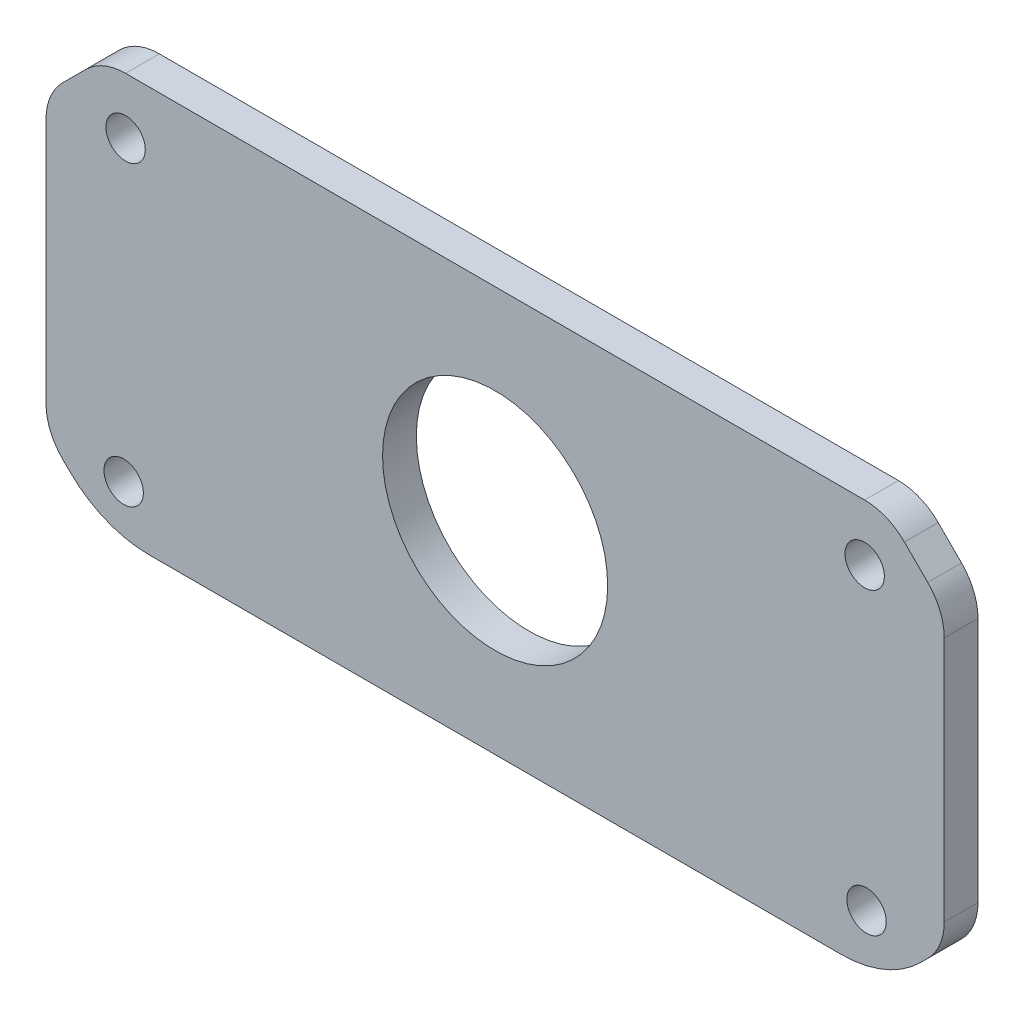
SolidWorks part; units mm, degrees
ref_plane "Front Plane" through (0, 0, 0) normal (0, 0, 1) x (1, 0, 0)
ref_plane "Top Plane" through (0, 0, 0) normal (0, 1, 0) x (1, 0, 0)
ref_plane "Right Plane" through (0, 0, 0) normal (1, 0, 0) x (0, 0, -1)
sketch "Sketch1" plane through (0, 0, 0) normal (0, 0, 1) x (1, 0, 0)
  line L0 (-39.9, -10.9289) -> (-39.9, 10.9289) construction
  line L1 (-39.9, -10.9289) -> (-39.9, 10.9289)
  line L2 (-34.9, -18) -> (-38.4355, -14.4645) construction
  line L3 (-34.9, -18) -> (-8.1, -18) construction
  line L4 (8.1, -18) -> (34.9, -18) construction
  line L5 (38.4355, -14.4645) -> (34.9, -18) construction
  line L6 (39.9, 10.9289) -> (39.9, -10.9289) construction
  line L7 (36.3645, 16.5355) -> (38.4355, 14.4645) construction
  line L8 (-32.8289, 18) -> (32.8289, 18) construction
  line L9 (-38.4355, 14.4645) -> (-36.3645, 16.5355) construction
  line L10 (-34.9, -18) -> (-38.4355, -14.4645)
  line L11 (-34.9, -18) -> (-8.1, -18)
  line L12 (8.1, -18) -> (34.9, -18)
  line L13 (38.4355, -14.4645) -> (34.9, -18)
  line L14 (39.9, 10.9289) -> (39.9, -10.9289)
  line L15 (36.3645, 16.5355) -> (38.4355, 14.4645)
  line L16 (-32.8289, 18) -> (32.8289, 18)
  line L17 (-38.4355, 14.4645) -> (-36.3645, 16.5355)
  line L18 (-8.1, -18) -> (8.1, -18)
  line L19 (0, 0) -> (0, 18) construction
  arc A0 (-39.9, -10.9289) -> (-38.4355, -14.4645) centre (-34.9, -10.9289) ccw construction
  arc A1 (38.4355, -14.4645) -> (39.9, -10.9289) centre (34.9, -10.9289) ccw construction
  arc A2 (39.9, 10.9289) -> (38.4355, 14.4645) centre (34.9, 10.9289) ccw construction
  arc A3 (36.3645, 16.5355) -> (32.8289, 18) centre (32.8289, 13) ccw construction
  arc A4 (-32.8289, 18) -> (-36.3645, 16.5355) centre (-32.8289, 13) ccw construction
  arc A5 (-38.4355, 14.4645) -> (-39.9, 10.9289) centre (-34.9, 10.9289) ccw construction
  arc A6 (-39.9, -10.9289) -> (-38.4355, -14.4645) centre (-34.9, -10.9289) ccw
  arc A7 (38.4355, -14.4645) -> (39.9, -10.9289) centre (34.9, -10.9289) ccw
  arc A8 (39.9, 10.9289) -> (38.4355, 14.4645) centre (34.9, 10.9289) ccw
  arc A9 (36.3645, 16.5355) -> (32.8289, 18) centre (32.8289, 13) ccw
  arc A10 (-32.8289, 18) -> (-36.3645, 16.5355) centre (-32.8289, 13) ccw
  arc A11 (-38.4355, 14.4645) -> (-39.9, 10.9289) centre (-34.9, 10.9289) ccw
  circle A12 centre (-32.8289, 13) radius 1.75
  circle A13 centre (-33, -13.5) radius 1.75
  circle A14 centre (33, -13.5) radius 1.75
  circle A15 centre (32.8289, 13) radius 1.75
  circle A16 centre (0, 0) radius 10
  dimension "D1" = 3.5
  dimension "D2" = 20
extrude "Boss-Extrude1" add sketch "Sketch1" along normal blind 3
fillet "Fillet1" radius 10 2 edges at (34.9, -18, 1.5) (-34.9, -18, 1.5)
